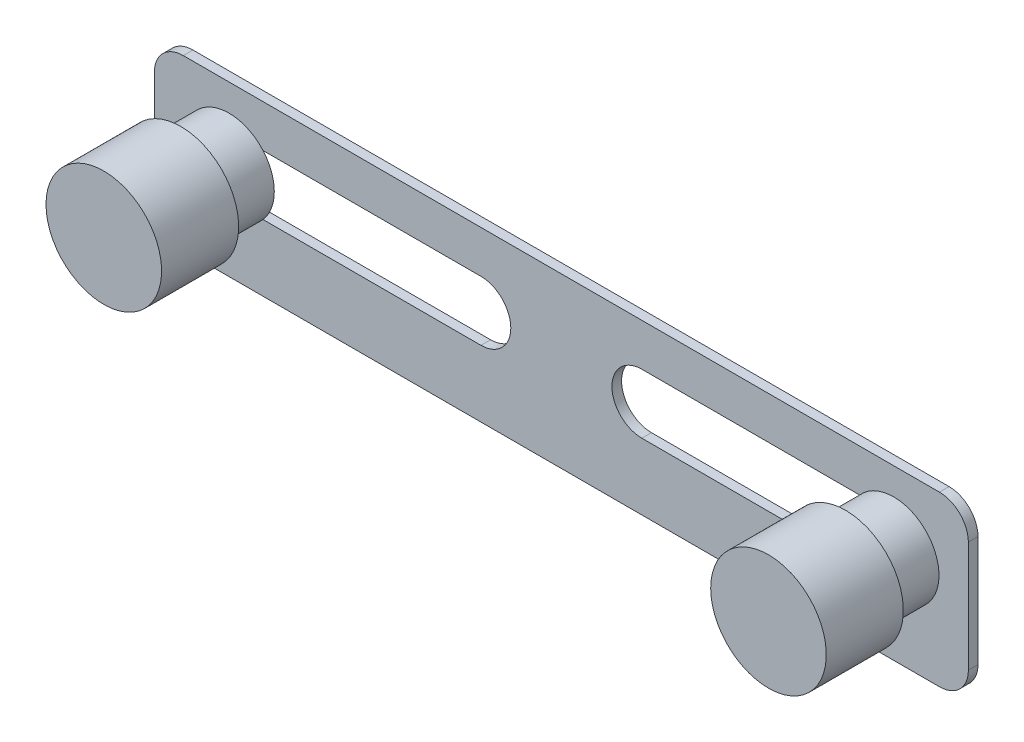
SolidWorks part; units mm, degrees
ref_plane "Front Plane" through (0, 0, 0) normal (0, 0, 1) x (1, 0, 0)
ref_plane "Top Plane" through (0, 0, 0) normal (0, 1, 0) x (1, 0, 0)
ref_plane "Right Plane" through (0, 0, 0) normal (1, 0, 0) x (0, 0, -1)
sketch "Sketch1" plane through (0, 0, 0) normal (0, 0, 1) x (1, 0, 0)
  line L0 (42.25, 17.5) -> (42.25, 0) construction
  line L1 (0, 0) -> (84.5, 0)
  line L2 (0, 0) -> (0, 17.5)
  line L3 (0, 17.5) -> (84.5, 17.5)
  line L4 (84.5, 0) -> (84.5, 17.5)
  line L5 (64.25, 13.1) -> (64.25, 6.9) construction
  line L6 (47.5, 13.1) -> (81, 13.1) construction
  line L7 (47.5, 13.1) -> (47.5, 6.9) construction
  line L8 (47.5, 6.9) -> (81, 6.9) construction
  line L9 (81, 13.1) -> (81, 6.9) construction
  line L10 (50.6, 13.1) -> (77.9, 13.1)
  line L11 (50.6, 6.9) -> (77.9, 6.9)
  line L12 (33.9, 13.1) -> (6.6, 13.1)
  line L13 (33.9, 6.9) -> (6.6, 6.9)
  arc A0 (50.6, 13.1) -> (50.6, 6.9) centre (50.6, 10) ccw
  arc A1 (77.9, 13.1) -> (77.9, 6.9) centre (77.9, 10) cw
  arc A2 (33.9, 13.1) -> (33.9, 6.9) centre (33.9, 10) cw
  arc A3 (6.6, 13.1) -> (6.6, 6.9) centre (6.6, 10) ccw
  point P11 (81, 10)
  dimension "D1" = 84.5
  dimension "D2" = 17.5
  dimension "D3" = 10
  dimension "D4" = 33.5
  dimension "D5" = 3.5
  dimension "D6" = 6.2
extrude "Boss-Extrude1" add sketch "Sketch1" along normal blind 1
fillet "Fillet1" radius 3 4 edges at (84.5, 17.5, 0.5) (84.5, 0, 0.5) (0, 0, 0.5) (0, 17.5, 0.5)
sketch "Sketch2" plane through (0, 0, 1) normal (0, 0, 1) x (1, 0, 0)
  line L0 (6.6, 6.9) -> (33.9, 6.9) construction
  line L1 (33.9, 13.1) -> (6.6, 13.1) construction
  line L2 (6.6, 6.9) -> (33.9, 6.9) construction
  line L3 (33.9, 13.1) -> (6.6, 13.1) construction
  line L4 (20.25, 13.1) -> (20.25, 6.9) construction
  line L5 (3.5, 10) -> (37, 10) construction
  arc A0 (6.6, 13.1) -> (6.6, 6.9) centre (6.6, 10) ccw construction
  arc A1 (33.9, 6.9) -> (33.9, 13.1) centre (33.9, 10) ccw construction
  arc A2 (6.6, 13.1) -> (6.6, 6.9) centre (6.6, 10) ccw construction
  arc A3 (33.9, 6.9) -> (33.9, 13.1) centre (33.9, 10) ccw construction
  circle A4 centre (7.75, 10) radius 6
  point P13 (20.25, 10)
  dimension "D1" = 12
  dimension "D2" = 12.5
extrude "Boss-Extrude2" add sketch "Sketch2" along normal blind 13
sketch "Sketch4" plane through (0, 0, 1) normal (0, 0, 1) x (1, 0, 0)
  circle A0 centre (7.75, 10) radius 4.7
  circle A1 centre (7.75, 10) radius 6
  circle A2 centre (7.75, 10) radius 6
  dimension "D2" = 9.4
  dimension "D1" = 0
extrude "Cut-Extrude1" cut sketch "Sketch4" along normal blind 5
ref_plane "Plane1" through (42.25, 0, 0) normal (1, 0, 0) x (0, 0, -1)
mirror "Mirror1" about plane through (42.25, 0, 0) normal (1, 0, 0) of "Cut-Extrude1", "Boss-Extrude2"
